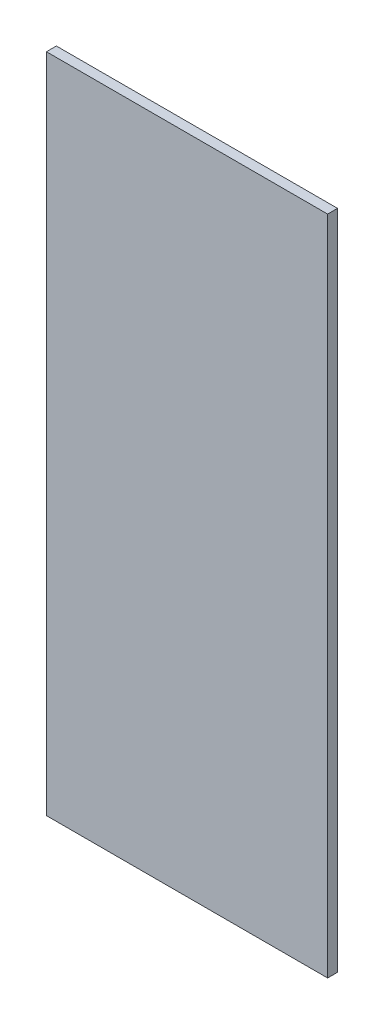
SolidWorks part; units mm, degrees
material "Pine"
ref_plane "Front Plane" through (0, 0, 0) normal (0, 0, 1) x (1, 0, 0)
ref_plane "Top Plane" through (0, 0, 0) normal (0, 1, 0) x (1, 0, 0)
ref_plane "Right Plane" through (0, 0, 0) normal (1, 0, 0) x (0, 0, -1)
sketch "Sketch1" plane through (0, 0, 0) normal (0, 0, 1) x (1, 0, 0)
  line L1 (-28.5714, 377.1048) -> (141.4286, 377.1048)
  line L2 (-28.5714, 377.1048) -> (-28.5714, -22.8952)
  line L3 (-28.5714, -22.8952) -> (141.4286, -22.8952)
  line L4 (141.4286, 377.1048) -> (141.4286, -22.8952)
  dimension "D1" = 400
  dimension "D2" = 170
extrude "Boss-Extrude1" add sketch "Sketch1" along normal blind 6
